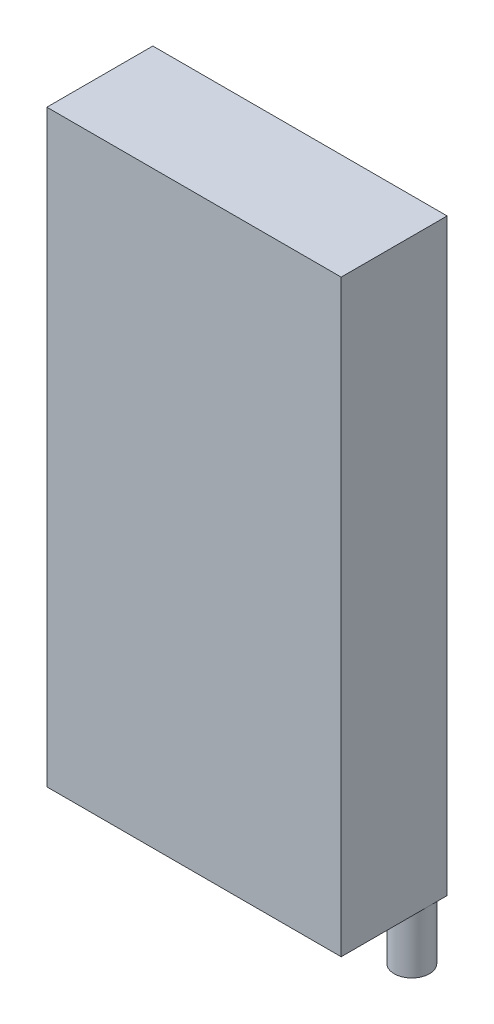
SolidWorks part; units mm, degrees
ref_plane "前视基准面" through (0, 0, 0) normal (0, 0, 1) x (1, 0, 0)
ref_plane "上视基准面" through (0, 0, 0) normal (0, 1, 0) x (1, 0, 0)
ref_plane "右视基准面" through (0, 0, 0) normal (1, 0, 0) x (0, 0, -1)
sketch "草图1" plane through (0, 0, 0) normal (0, 0, 1) x (1, 0, 0)
  line L1 (-12.5, 25) -> (12.5, 25)
  line L2 (-12.5, 25) -> (-12.5, -25)
  line L3 (-12.5, -25) -> (12.5, -25)
  line L4 (12.5, 25) -> (12.5, -25)
  line L5 (-12.5, 25) -> (12.5, -25) construction
  line L6 (-12.5, -25) -> (12.5, 25) construction
  point P0 (0, 0)
extrude "凸台-拉伸1" add sketch "草图1" along normal blind 9
sketch "草图2" plane through (0, -25, 0) normal (0, -1, 0) x (1, 0, 0)
  circle A2 centre (-11, 1.5) radius 1.5
  circle A3 centre (11, 1.5) radius 1.5
extrude "凸台-拉伸3" add sketch "草图2" along normal blind 5
